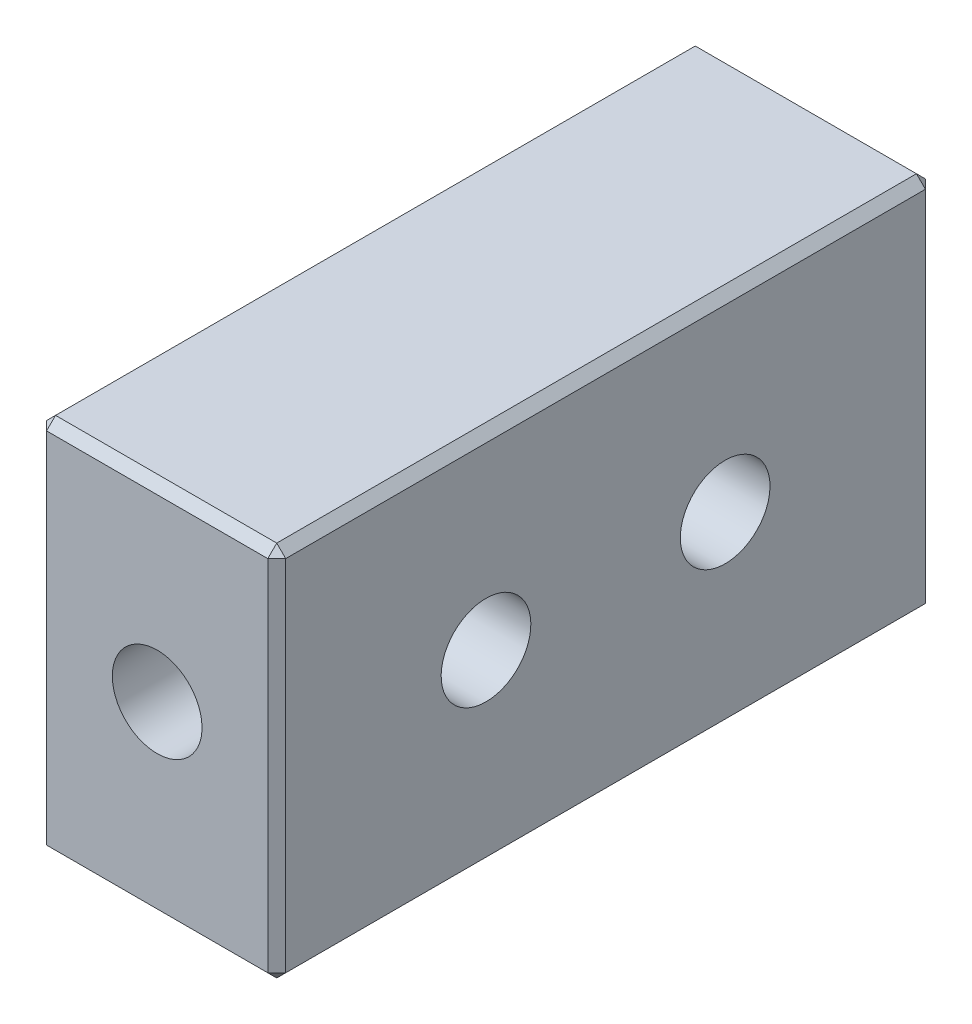
SolidWorks part; units mm, degrees
material "6061 合金"
ref_plane "前视基准面" through (0, 0, 0) normal (0, 0, 1) x (1, 0, 0)
ref_plane "上视基准面" through (0, 0, 0) normal (0, 1, 0) x (1, 0, 0)
ref_plane "右视基准面" through (0, 0, 0) normal (1, 0, 0) x (0, 0, -1)
sketch "草图1" plane through (0, 0, 0) normal (0, 0, 1) x (1, 0, 0)
  line L1 (-4, 6.3) -> (4, 6.3)
  line L2 (-4, 6.3) -> (-4, -6.3)
  line L3 (-4, -6.3) -> (4, -6.3)
  line L4 (4, 6.3) -> (4, -6.3)
  line L5 (-4, 6.3) -> (4, -6.3) construction
  line L6 (-4, -6.3) -> (4, 6.3) construction
  point P0 (0, 0)
  dimension "D1" = 12.6
  dimension "D2" = 8
extrude "凸台-拉伸1" add sketch "草图1" along normal blind 22
chamfer "倒角1" distance 0.3 angle 45 12 edges at (0, -6.3, 0) (-4, -6.3, 11) (-4, 0, 0) (0, -6.3, 22) (-4, 0, 22) (4, -6.3, 11) (4, 0, 22) (4, 0, 0) (4, 6.3, 11) (0, 6.3, 22) (-4, 6.3, 11) (0, 6.3, 0)
sketch "草图2" plane through (-4, 0, 0) normal (-1, 0, 0) x (0, 0, 1)
  line L0 (0, 0) -> (22, 0) construction
  line L1 (22, 6) -> (22, -6) construction
  line L2 (11, 0) -> (11, 6) construction
  line L3 (21.7, 6) -> (0.3, 6) construction
  circle A0 centre (15, 0) radius 1.5
  circle A1 centre (7, 0) radius 1.5
  dimension "D1" = 3
  dimension "D2" = 4
extrude "切除-拉伸1" cut sketch "草图2" against normal through all
sketch "草图3" plane through (0, 0, 0) normal (0, 0, -1) x (-1, 0, 0)
  circle A0 centre (0, 0) radius 1.5
  dimension "D1" = 3
extrude "切除-拉伸2" cut sketch "草图3" against normal blind 4
ref_plane "基准面1" [suppressed] through (0, 0, 11) normal (0, 0, -1) x (-1, 0, 0)
mirror "镜向1" about plane through (0, 0, 11) normal (0, 0, -1) of "切除-拉伸2"
